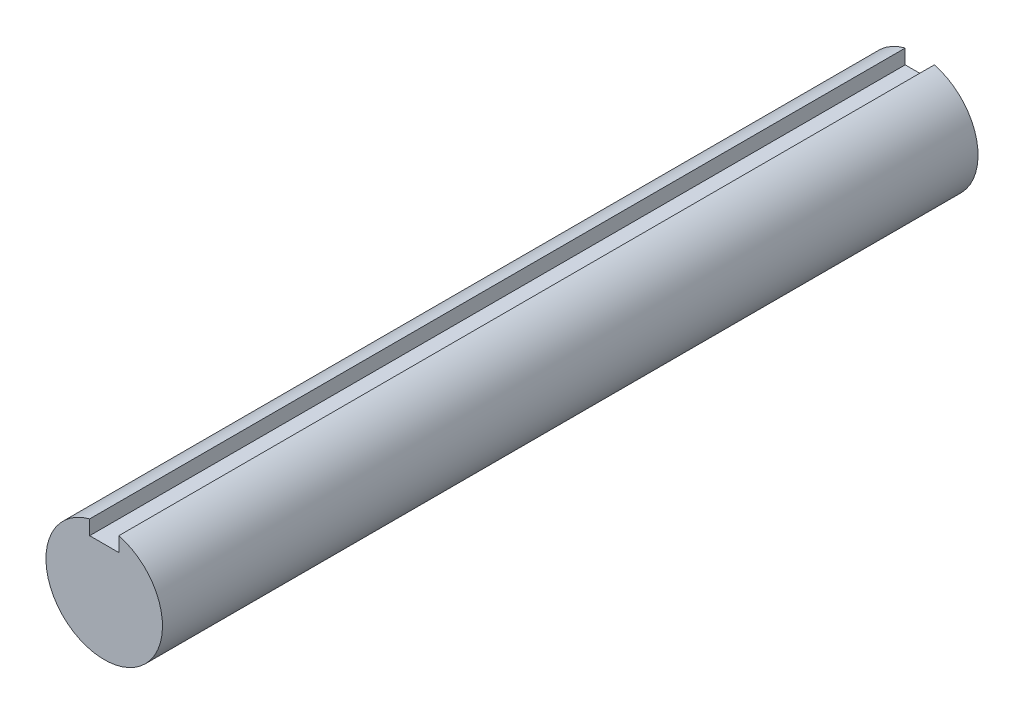
SolidWorks part; units mm, degrees
ref_plane "Front Plane" through (0, 0, 0) normal (0, 0, 1) x (1, 0, 0)
ref_plane "Top Plane" through (0, 0, 0) normal (0, 1, 0) x (1, 0, 0)
ref_plane "Right Plane" through (0, 0, 0) normal (1, 0, 0) x (0, 0, -1)
sketch "Sketch1" plane through (0, 0, 0) normal (0, 0, 1) x (1, 0, 0)
  line L3 (1.1906, 3.4206) -> (-1.1906, 3.4206)
  line L5 (1.1906, 3.4206) -> (1.1906, 4.6113)
  line L7 (-1.1906, 3.4206) -> (-1.1906, 4.6113)
  line L9 (0, 4.46) -> (-1.1906, 3.4206) construction
  arc A0 (-1.1906, 4.6113) -> (1.1906, 4.6113) centre (0, 0) ccw
  point P3 (0, 4.7625)
  point P4 (0, 4.46)
  dimension "D1" = 9.525
  dimension "D2" = 2.3812
  dimension "D3" = 1.1906
  dimension "D4" = 1.1906
extrude "Boss-Extrude1" add sketch "Sketch1" along normal blind 66.675
